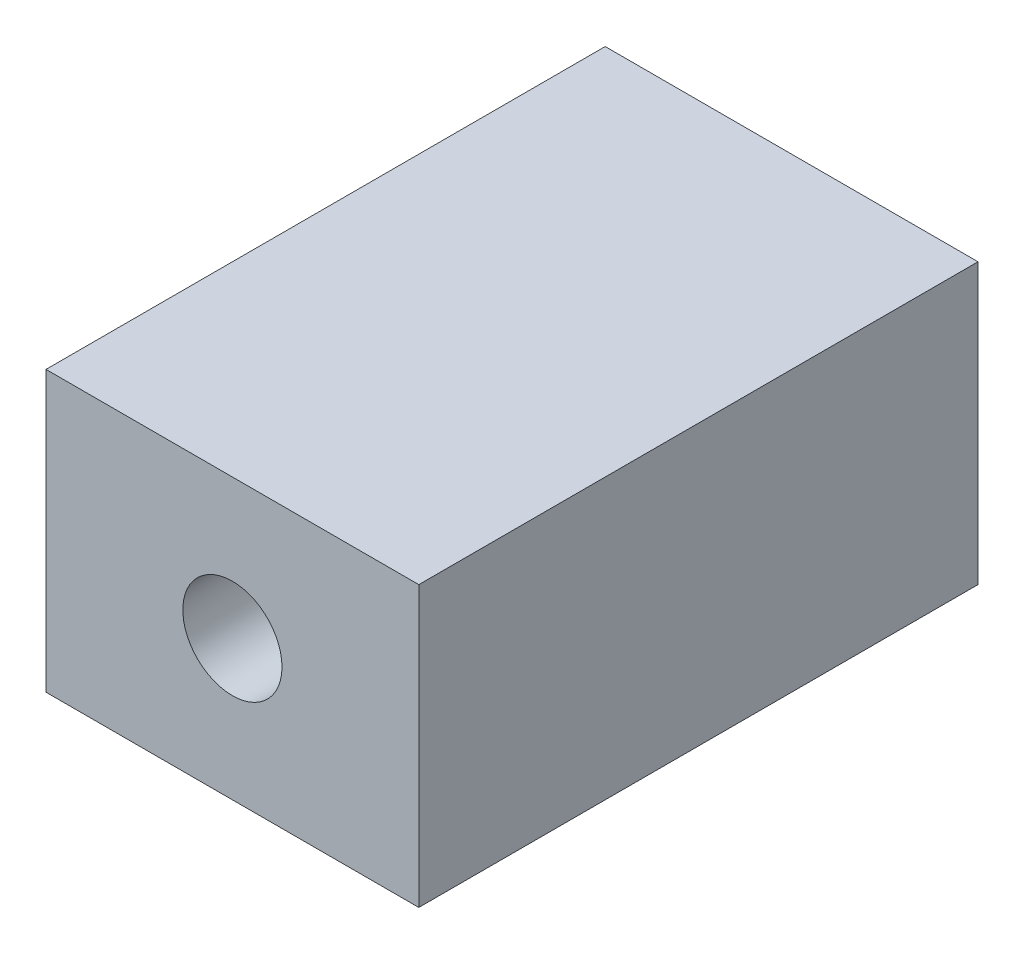
SolidWorks part; units mm, degrees
ref_plane "Front Plane" through (0, 0, 0) normal (0, 0, 1) x (1, 0, 0)
ref_plane "Top Plane" through (0, 0, 0) normal (0, 1, 0) x (1, 0, 0)
ref_plane "Right Plane" through (0, 0, 0) normal (1, 0, 0) x (0, 0, -1)
sketch "Sketch1" plane through (0, 0, 0) normal (0, 1, 0) x (1, 0, 0)
  line L1 (-12.7, -19.05) -> (12.7, -19.05)
  line L2 (-12.7, -19.05) -> (-12.7, 19.05)
  line L3 (-12.7, 19.05) -> (12.7, 19.05)
  line L4 (12.7, -19.05) -> (12.7, 19.05)
  line L5 (-12.7, -19.05) -> (12.7, 19.05) construction
  line L6 (-12.7, 19.05) -> (12.7, -19.05) construction
  point P0 (0, 0)
  dimension "D1" = 38.1
  dimension "D2" = 25.4
extrude "Boss-Extrude1" add sketch "Sketch1" along normal mid plane 19.05
sketch "Sketch2" plane through (0, 0, 19.05) normal (0, 0, 1) x (1, 0, 0)
  line L0 (0, -55) -> (0, 55) construction
  line L1 (55, 0) -> (-55, 0) construction
  point P0 (0, 0)
hole_wizard "1/4 Clearance Hole1" positions "Sketch3" profile "Sketch4" hole size "1/4" standard "ANSI Inch" end condition through all
sketch "Sketch3" plane through (0, 0, 19.05) normal (0, 0, 1) x (1, 0, 0)
  point P0 (0, 0)
sketch "Sketch4" plane through (0, 0, 19.05) normal (1, 0, 0) x (0, -1, 0)
  line L0 (0, 0) -> (0, 38.1)
  line L1 (0, 38.1) -> (3.3782, 38.1)
  line L2 (3.3782, 38.1) -> (3.3782, 0)
  line L5 (3.3782, 0) -> (0, 0)
  line L11 (0, -6.35) -> (0, 107.95) construction
  dimension "Thru Hole Dia." = 6.7564
  dimension "Thru Hole Depth" = 38.1
sketch "Sketch5" plane through (0, -9.525, 0) normal (0, -1, 0) x (1, 0, 0)
  line L0 (-8.89, 12.7) -> (-8.89, -12.7) construction
  line L1 (-8.89, -12.7) -> (8.89, -12.7) construction
  line L2 (10.4775, 0) -> (-10.4775, 0) construction
  line L3 (0, -10.4775) -> (0, 10.4775) construction
  line L4 (12.7, 19.05) -> (12.7, -19.05) construction
  line L5 (12.7, -19.05) -> (-12.7, -19.05) construction
  point P0 (-8.89, 12.7)
  point P1 (8.89, -12.7)
  point P5 (-8.89, 0)
  point P8 (0, -12.7)
  dimension "D1" = 3.81
  dimension "D2" = 6.35
hole_wizard "#8-32 Tapped Hole1" positions "Sketch6" profile "Sketch7" tap size "#8-32" standard "ANSI Inch"
sketch "Sketch6" plane through (0, -9.525, 0) normal (0, -1, 0) x (-1, 0, 0)
  point P0 (8.89, -12.7)
  point P3 (-8.89, 12.7)
sketch "Sketch7" plane through (-8.89, -9.525, 12.7) normal (1, 0, 0) x (0, 0, -1)
  line L0 (0, 0) -> (0, 11.7058)
  line L1 (0, 11.7058) -> (1.7272, 10.668)
  line L2 (1.7272, 10.668) -> (1.7272, 0)
  line L5 (1.7272, 0) -> (0, 0)
  line L10 (0, 11.7058) -> (-1.7272, 10.668) construction
  line L11 (0, -6.35) -> (0, 107.95) construction
  dimension "Tap Drill Dia." = 3.4544
  dimension "Tap Drill Depth" = 10.668
  dimension "Drill Angle" = 118
cosmetic thread "Hole Thread2" parameters "D1"=8.382, "D2"=4.1656
cosmetic thread "Hole Thread3" parameters "D1"=8.382, "D2"=4.1656
